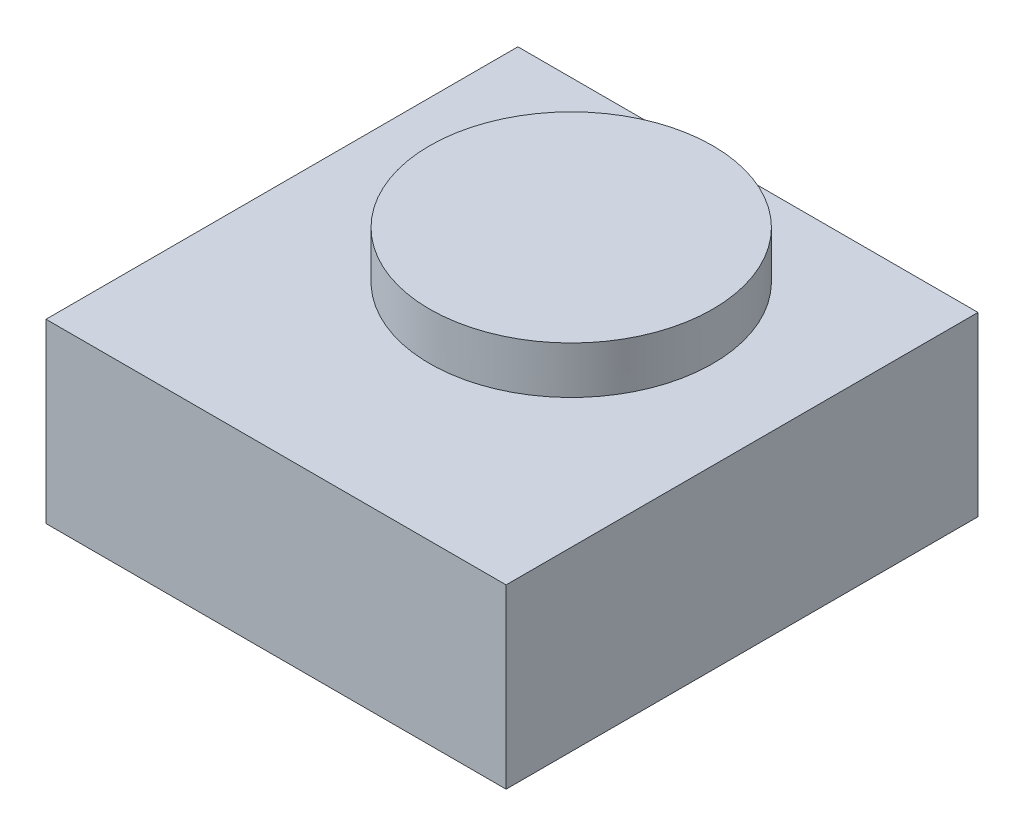
SolidWorks part; units mm, degrees
ref_plane "Front Plane" through (0, 0, 0) normal (0, 0, 1) x (1, 0, 0)
ref_plane "Top Plane" through (0, 0, 0) normal (0, 1, 0) x (1, 0, 0)
ref_plane "Right Plane" through (0, 0, 0) normal (1, 0, 0) x (0, 0, -1)
sketch "Sketch1" plane through (0, 0, 0) normal (0, 1, 0) x (1, 0, 0)
  line L1 (0, 0) -> (123.825, 0)
  line L2 (0, 0) -> (0, 127)
  line L3 (0, 127) -> (123.825, 127)
  line L4 (123.825, 0) -> (123.825, 127)
  dimension "D1" = 123.825
  dimension "D2" = 127
extrude "Boss-Extrude1" add sketch "Sketch1" along normal blind 47.625
sketch "Sketch2" plane through (0, 47.625, 0) normal (0, 1, 0) x (1, 0, 0)
  line L0 (123.825, 127) -> (0, 127) construction
  circle A0 centre (61.976, 79.375) radius 38.1
  dimension "D1" = 76.2
  dimension "D2" = 47.625
  dimension "D3" = 61.976
extrude "Boss-Extrude2" add sketch "Sketch2" along normal blind 12.7
